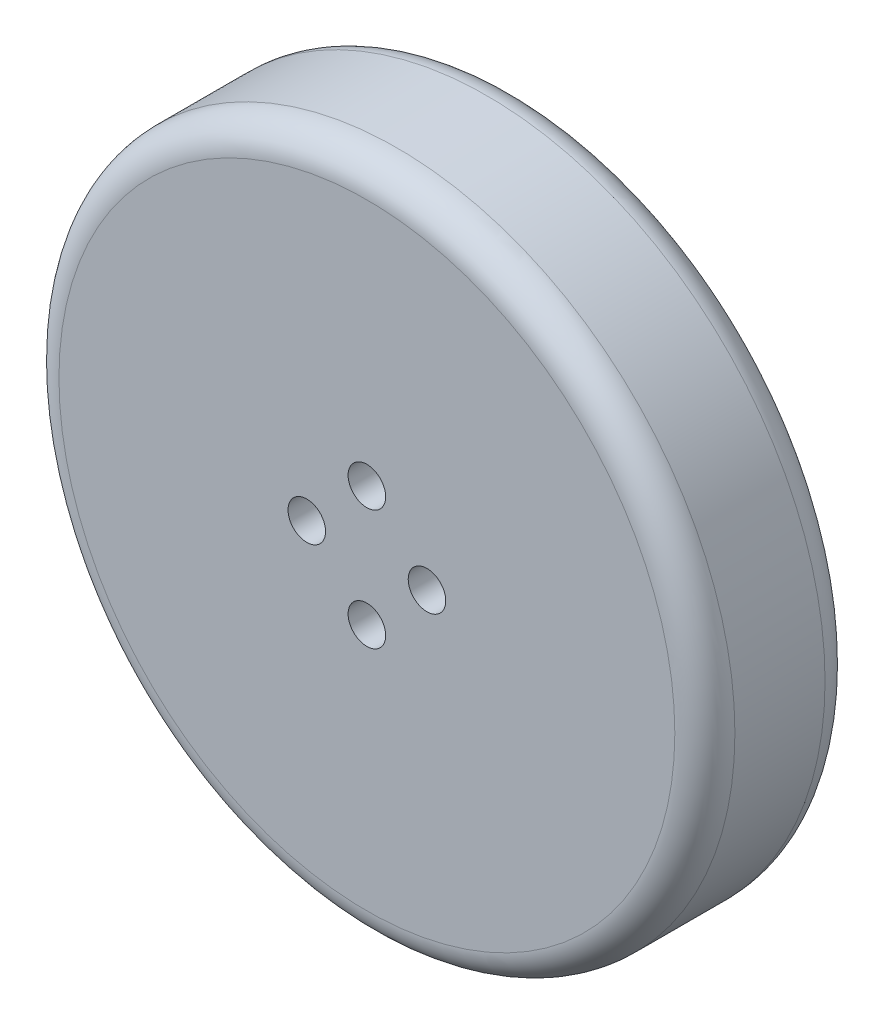
SolidWorks part; units mm, degrees
ref_plane "Front Plane" through (0, 0, 0) normal (0, 0, 1) x (1, 0, 0)
ref_plane "Top Plane" through (0, 0, 0) normal (0, 1, 0) x (1, 0, 0)
ref_plane "Right Plane" through (0, 0, 0) normal (1, 0, 0) x (0, 0, -1)
sketch "Sketch2" plane through (0, 0, 0) normal (0, 0, 1) x (1, 0, 0)
  circle A0 centre (0, 0) radius 4 construction
  circle A1 centre (4, 0) radius 1.25
  circle A2 centre (0, 4) radius 1.25
  circle A3 centre (-4, 0) radius 1.25
  circle A4 centre (0, -4) radius 1.25
  circle A5 centre (0, 0) radius 22.5
  point P12 (0, -22.5)
  dimension "D1" = 8
  dimension "D2" = 2.5
  dimension "D3" = 45
extrude "Boss-Extrude1" add sketch "Sketch2" along normal blind 10
sketch "Sketch3" plane through (0, 0, 0) normal (0, 0, -1) x (-1, 0, 0)
  circle A0 centre (0, 0) radius 10
  dimension "D1" = 20
extrude "Cut-Extrude1" cut sketch "Sketch3" against normal blind 4
fillet "Fillet1" radius 2 2 edges at (22.5, 0, 0) (22.5, 0, 10)
